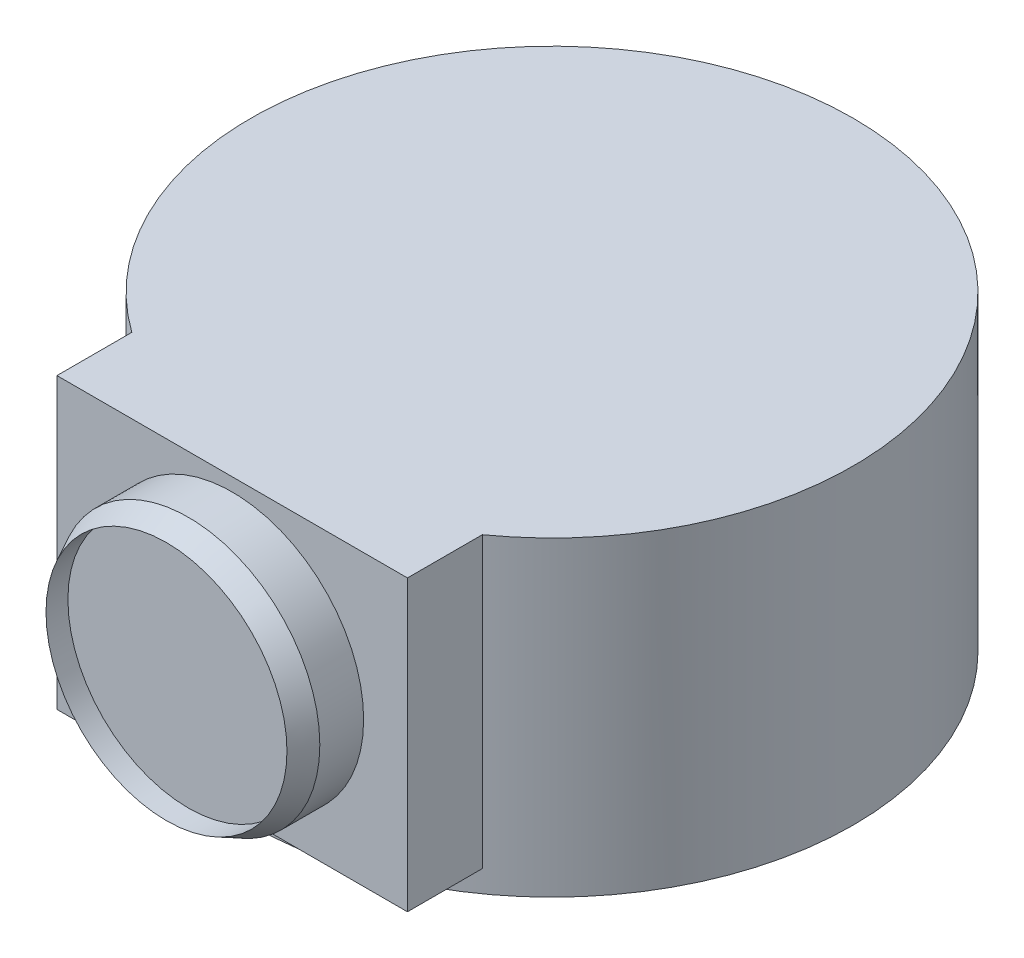
SolidWorks part; units mm, degrees
ref_plane "Front Plane" through (0, 0, 0) normal (0, 0, 1) x (1, 0, 0)
ref_plane "Top Plane" through (0, 0, 0) normal (0, 1, 0) x (1, 0, 0)
ref_plane "Right Plane" through (0, 0, 0) normal (1, 0, 0) x (0, 0, -1)
sketch "Sketch1" plane through (0, 0, 0) normal (0, 1, 0) x (1, 0, 0)
  circle A0 centre (0, 0) radius 68.75
extrude "Boss-Extrude1" add sketch "Sketch1" along normal blind 66
sketch "Sketch2" plane through (0, 0, 0) normal (0, 0, 1) x (1, 0, 0)
  line L0 (0, 0) -> (-80, 0) construction
  line L1 (-68.75, 0) -> (68.75, 0) construction
  line L3 (-40, 0) -> (-40, 66)
  line L7 (0, 0) -> (-40, 0)
  line L8 (68.75, 66) -> (-68.75, 66) construction
  line L9 (-40, 66) -> (40, 66)
  line L10 (40, 66) -> (40, 0)
  line L11 (40, 0) -> (-40, 0)
  line L12 (0, 0) -> (40, 0)
extrude "Boss-Extrude3" add sketch "Sketch2" along normal blind 83 contours L11 L10 L9 L3 L7
sketch "Sketch3" plane through (0, 0, 83) normal (0, 0, 1) x (1, 0, 0)
  line L0 (0, 0) -> (0, 33) construction
  line L3 (40, 0) -> (-40, 0) construction
  circle A1 centre (0, 33) radius 30
sketch "Sketch4" plane through (0, 0, 0) normal (1, 0, 0) x (0, 0, -1)
  line L0 (-83, 33) -> (-83, 5.5)
  line L1 (-83, 63) -> (-83, 3) construction
  line L2 (-83, 0) -> (-83, 33) construction
  line L3 (-83, 5.5) -> (-88, 5.5)
  line L4 (-83, 5.5) -> (-83, 3)
  line L5 (-83, 3) -> (-88, 5.5)
  line L6 (-83, 33) -> (-70.1732, 33) construction
  point P6 (-94.8383, 2.9678)
revolve "Revolve1" add sketch "Sketch4" angle 360 about L6
sketch "Sketch5" plane through (0, 0, 83) normal (0, 0, 1) x (1, 0, 0)
  circle A0 centre (0, 33) radius 30
  circle A1 centre (0, 33) radius 56.243
extrude "Cut-Extrude2" cut sketch "Sketch5" against normal blind 10
sketch "Sketch6" plane through (0, 0, 0) normal (0, -1, 0) x (-1, 0, 0)
  circle A0 centre (0, 0) radius 68.75
extrude "Boss-Extrude4" add sketch "Sketch6" along normal blind 5
